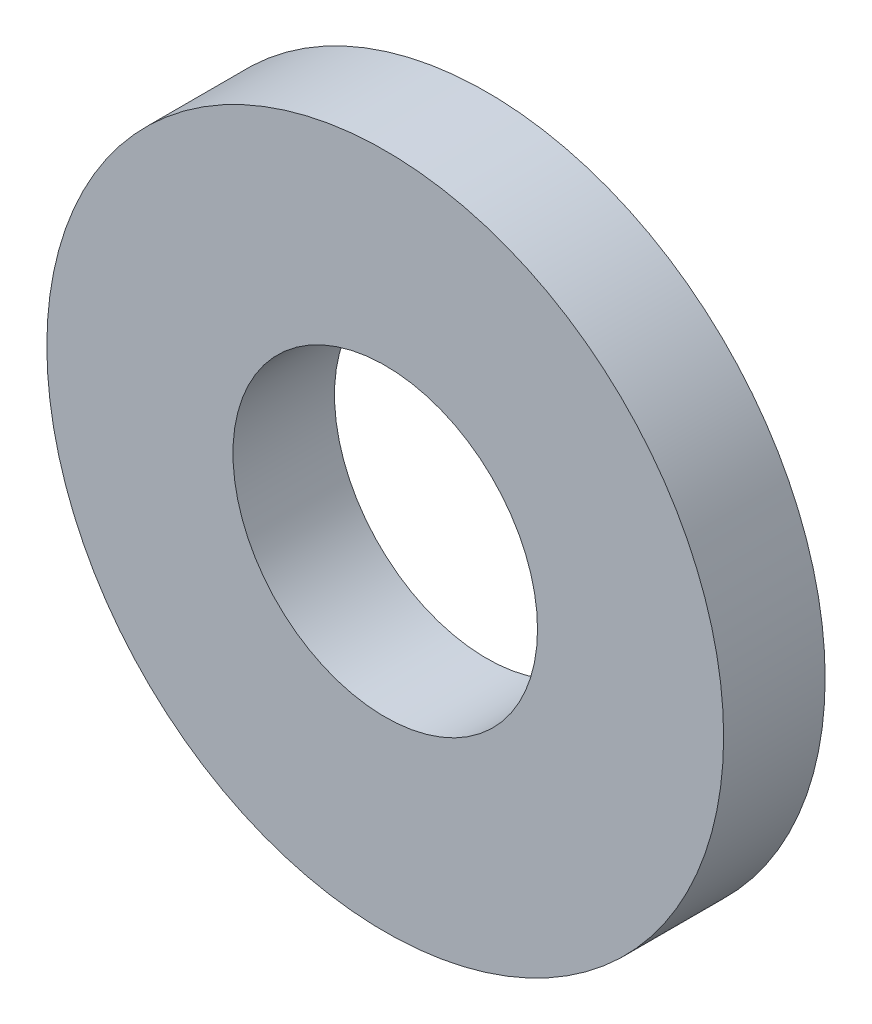
SolidWorks part; units mm, degrees
ref_plane "정면" through (0, 0, 0) normal (0, 0, 1) x (1, 0, 0)
ref_plane "윗면" through (0, 0, 0) normal (0, 1, 0) x (1, 0, 0)
ref_plane "우측면" through (0, 0, 0) normal (1, 0, 0) x (0, 0, -1)
sketch "스케치1" plane through (0, 0, 0) normal (0, 0, 1) x (1, 0, 0)
  circle A0 centre (0, 0) radius 5
  circle A1 centre (0, 0) radius 2.25
  dimension "D1" = 10
  dimension "D2" = 4.5
extrude "보스-돌출1" add sketch "스케치1" along normal blind 1.5
